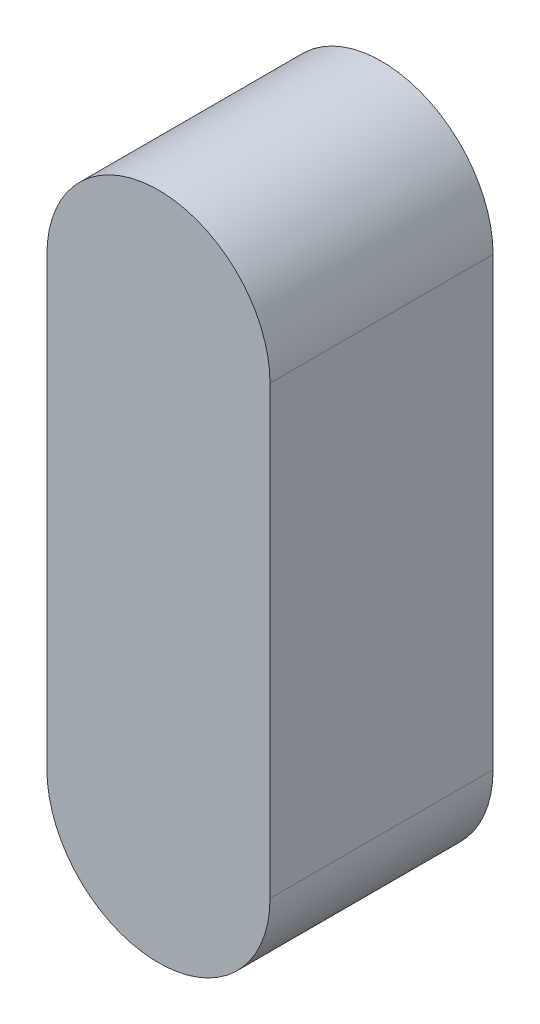
SolidWorks part; units mm, degrees
ref_plane "Płaszczyzna przednia" through (0, 0, 0) normal (0, 0, 1) x (1, 0, 0)
ref_plane "Płaszczyzna górna" through (0, 0, 0) normal (0, 1, 0) x (1, 0, 0)
ref_plane "Płaszczyzna prawa" through (0, 0, 0) normal (1, 0, 0) x (0, 0, -1)
sketch "Szkic1" plane through (0, 0, 0) normal (0, 0, 1) x (1, 0, 0)
  line L0 (0, 0) -> (0, 10) construction
  line L1 (-2.5, 0) -> (-2.5, 10)
  line L2 (2.5, 0) -> (2.5, 10)
  arc A0 (-2.5, 0) -> (2.5, 0) centre (0, 0) ccw
  arc A1 (2.5, 10) -> (-2.5, 10) centre (0, 10) ccw
  point P3 (0, 5)
  dimension "D1" = 10
  dimension "D2" = 5
extrude "Dodanie-wyciągnięcie1" add sketch "Szkic1" along normal blind 5
